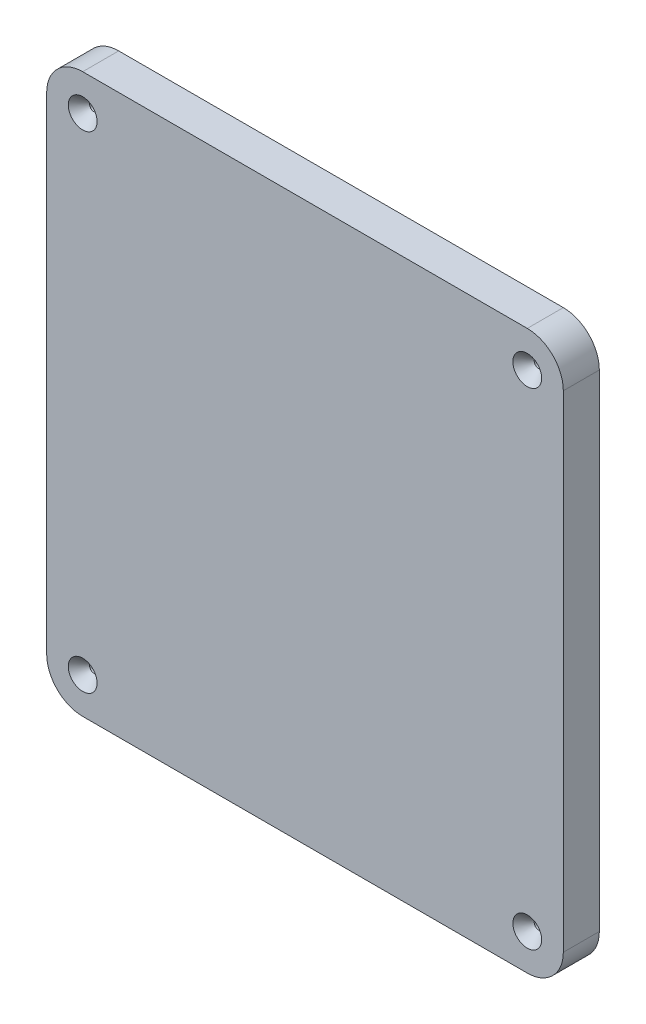
SolidWorks part; units mm, degrees
material "Beech"
ref_plane "Front Plane" through (0, 0, 0) normal (0, 0, 1) x (1, 0, 0)
ref_plane "Top Plane" through (0, 0, 0) normal (0, 1, 0) x (1, 0, 0)
ref_plane "Right Plane" through (0, 0, 0) normal (1, 0, 0) x (0, 0, -1)
sketch "Sketch1" plane through (0, 0, 0) normal (0, 0, 1) x (1, 0, 0)
  line L0 (139.05, 899.8522) -> (139.05, 151.949) construction
  line L1 (-43.1, 899.8522) -> (-43.1, 151.949) construction
  line L2 (-43.1, 906.2022) -> (139.05, 906.2022) construction
  line L8 (139.05, 668.0772) -> (139.05, 864.9272)
  line L9 (139.05, 864.9272) -> (-43.1, 864.9272)
  line L10 (-43.1, 864.9272) -> (-43.1, 668.0772)
  line L11 (-43.1, 668.0772) -> (139.05, 668.0772)
  dimension "D1" = 196.85
  dimension "D2" = 41.275
extrude "Boss-Extrude1" add sketch "Sketch1" along normal blind 12.7
fillet "Fillet1" radius 12.7 4 edges at (139.05, 864.9272, 6.35) (139.05, 668.0772, 6.35) (-43.1, 668.0772, 6.35) (-43.1, 864.9272, 6.35)
hole_wizard "Hole1" positions "Sketch2" profile "Sketch3" legacy
sketch "Sketch2" plane through (47.975, -440.812, 12.7) normal (0, 0, 1) x (1, 0, 0)
  point P0 (-78.375, 1293.0392)
  point P3 (-78.375, 1121.5892)
  point P6 (78.375, 1121.5892)
  point P9 (78.375, 1293.0392)
  point P12 (-764.0155, 1530.0782)
sketch "Sketch3" plane through (-30.4, 852.2272, 12.7) normal (1, 0, 0) x (0, -1, 0)
  line L0 (0, 0) -> (0, 32.7039)
  line L1 (0, 32.7039) -> (1.5875, 31.75)
  line L2 (1.5875, 31.75) -> (1.5875, 4.0177)
  line L3 (1.5875, 4.0177) -> (5.08, 0)
  line L4 (5.08, 0) -> (0, 0)
  line L5 (0, -14.3089) -> (0, 102.4216) construction
  line L6 (0, 32.7039) -> (-1.5875, 31.75) construction
  line L7 (-1.5875, 4.0177) -> (-5.08, 0) construction
  dimension "Diameter" = 3.175
  dimension "Depth" = 31.75
  dimension "C-Sink Diameter" = 10.16
  dimension "C-Sink Angle" = 82
  dimension "Drill Angle" = 118
